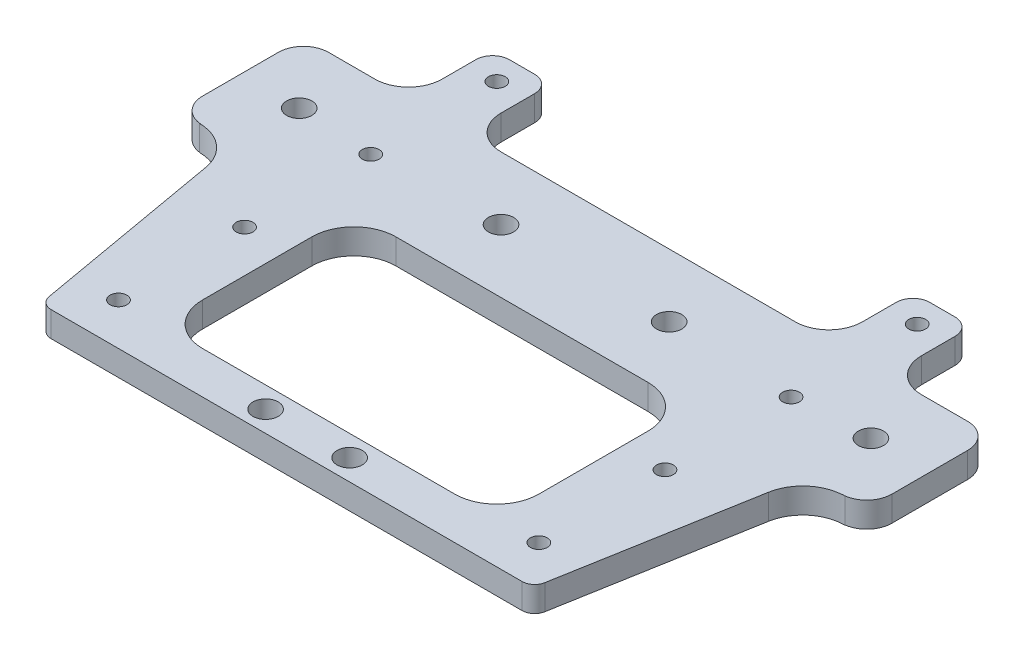
SolidWorks part; units mm, degrees
material "Thornel Mat VMA"
ref_plane "前视基准面" through (0, 0, 0) normal (0, 0, 1) x (1, 0, 0)
ref_plane "上视基准面" through (0, 0, 0) normal (0, 1, 0) x (1, 0, 0)
ref_plane "右视基准面" through (0, 0, 0) normal (1, 0, 0) x (0, 0, -1)
sketch "草图1" plane through (0, 0, 0) normal (0, 1, 0) x (1, 0, 0)
  line L0 (0, 33.9286) -> (0, -25) construction
  line L1 (-23.5, 0) -> (23.5, 0) construction
  line L2 (-28.5, -2) -> (-28.5, -6)
  line L3 (25, 0) -> (25, -48) construction
  line L4 (-26.5, 0) -> (-23.5, 0)
  line L5 (-21.5, -2) -> (-21.5, -6)
  line L6 (-17.5, -10) -> (17.5, -10)
  line L7 (-38, -25) -> (-38.3913, -25)
  line L8 (-25, 0) -> (-25, -48) construction
  line L9 (-34, -17.5) -> (34, -17.5) construction
  line L10 (41, -13) -> (41, -22)
  line L11 (32.5, -10) -> (38, -10)
  line L12 (21.5, -2) -> (21.5, -6)
  line L13 (-32.5, -10) -> (-38, -10)
  line L14 (-41, -13) -> (-41, -22)
  line L15 (-33.4673, -29.1318) -> (-29.4772, -51.7605)
  line L16 (26.5, 0) -> (23.5, 0)
  line L17 (28.5, -2) -> (28.5, -6)
  line L18 (-28, -53) -> (-22, -53)
  line L19 (-20, -43) -> (-20, -30)
  line L20 (-15, -25) -> (15, -25)
  line L21 (20, -43) -> (20, -30)
  line L22 (28, -53) -> (22, -53)
  line L23 (33.4673, -29.1318) -> (29.4772, -51.7605)
  line L24 (38.3913, -25) -> (38, -25)
  line L25 (-22, -53) -> (22, -53)
  line L26 (-15, -48) -> (15, -48)
  line L27 (-5, -50.5) -> (5, -50.5) construction
  arc A0 (-21.5, -6) -> (-17.5, -10) centre (-17.5, -6) ccw
  circle A1 centre (-25, -48) radius 1
  circle A2 centre (-25, -33) radius 1
  circle A3 centre (-25, -18) radius 1
  circle A4 centre (-34, -17.5) radius 1.5
  arc A5 (-28.5, -6) -> (-32.5, -10) centre (-32.5, -6) cw
  arc A6 (-23.5, 0) -> (-21.5, -2) centre (-23.5, -2) cw
  arc A7 (26.5, 0) -> (28.5, -2) centre (26.5, -2) cw
  arc A8 (38, -10) -> (41, -13) centre (38, -13) cw
  arc A9 (41, -22) -> (38, -25) centre (38, -22) cw
  arc A10 (-29.4772, -51.7605) -> (-28, -53) centre (-28, -51.5) ccw
  circle A11 centre (-10, -17.5) radius 1.5
  arc A12 (21.5, -6) -> (17.5, -10) centre (17.5, -6) cw
  arc A13 (28.5, -6) -> (32.5, -10) centre (32.5, -6) ccw
  circle A14 centre (10, -17.5) radius 1.5
  arc A15 (23.5, 0) -> (21.5, -2) centre (23.5, -2) ccw
  circle A16 centre (34, -17.5) radius 1.5
  circle A17 centre (25, -18) radius 1
  circle A18 centre (25, -33) radius 1
  circle A19 centre (25, -48) radius 1
  arc A20 (15, -48) -> (20, -43) centre (15, -43) ccw
  arc A21 (-41, -22) -> (-38, -25) centre (-38, -22) ccw
  arc A22 (-38, -10) -> (-41, -13) centre (-38, -13) ccw
  arc A23 (-26.5, 0) -> (-28.5, -2) centre (-26.5, -2) ccw
  arc A24 (-15, -48) -> (-20, -43) centre (-15, -43) cw
  arc A25 (29.4772, -51.7605) -> (28, -53) centre (28, -51.5) cw
  arc A26 (33.4673, -29.1318) -> (38.3913, -25) centre (38.3913, -30) cw
  arc A27 (20, -30) -> (15, -25) centre (15, -30) ccw
  arc A28 (-33.4673, -29.1318) -> (-38.3913, -25) centre (-38.3913, -30) ccw
  arc A29 (-20, -30) -> (-15, -25) centre (-15, -30) cw
  circle A30 centre (-25, -3) radius 1
  circle A31 centre (25, -3) radius 1
  circle A32 centre (5, -50.5) radius 1.5
  circle A33 centre (-5, -50.5) radius 1.5
  point P25 (-38, -25)
  point P26 (-28.5, -10)
  point P44 (-21.5, 0)
  point P47 (0, -10)
  point P52 (-25, 0)
  point P54 (0, -10)
  point P71 (41, -10)
  point P74 (28.5, -10)
  point P82 (-41, -10)
  point P92 (34.1958, -25)
  point P95 (20, -25)
  point P98 (-34.1958, -25)
  point P101 (-20, -25)
  point P107 (0, -50.5)
  point P110 (-41, -17.5)
  dimension "D8" = 2
  dimension "D10" = 5
  dimension "D11" = 10
  dimension "D15" = 3
  dimension "D16" = 2
  dimension "D22" = 3
  dimension "D17" = 4
  dimension "D24" = 2
  dimension "D28" = 5
  dimension "D19" = 1.5
  dimension "D14" = 4
  dimension "D23" = 15
  dimension "D18" = 3
  dimension "D20" = 5
  dimension "D31" = 3
  dimension "D32" = 5
  dimension "D4" = 3
  dimension "D6" = 7
  dimension "D9" = 23
  dimension "D12" = 15
  dimension "D13" = 15
  dimension "D21" = 7
  dimension "D25" = 25
  dimension "D26" = 15
  dimension "D27" = 9
  dimension "D29" = 10
  dimension "D30" = 5
  dimension "D33" = 10
  dimension "D34" = 2.5
extrude "凸台-拉伸1" add sketch "草图1" along normal blind 3
